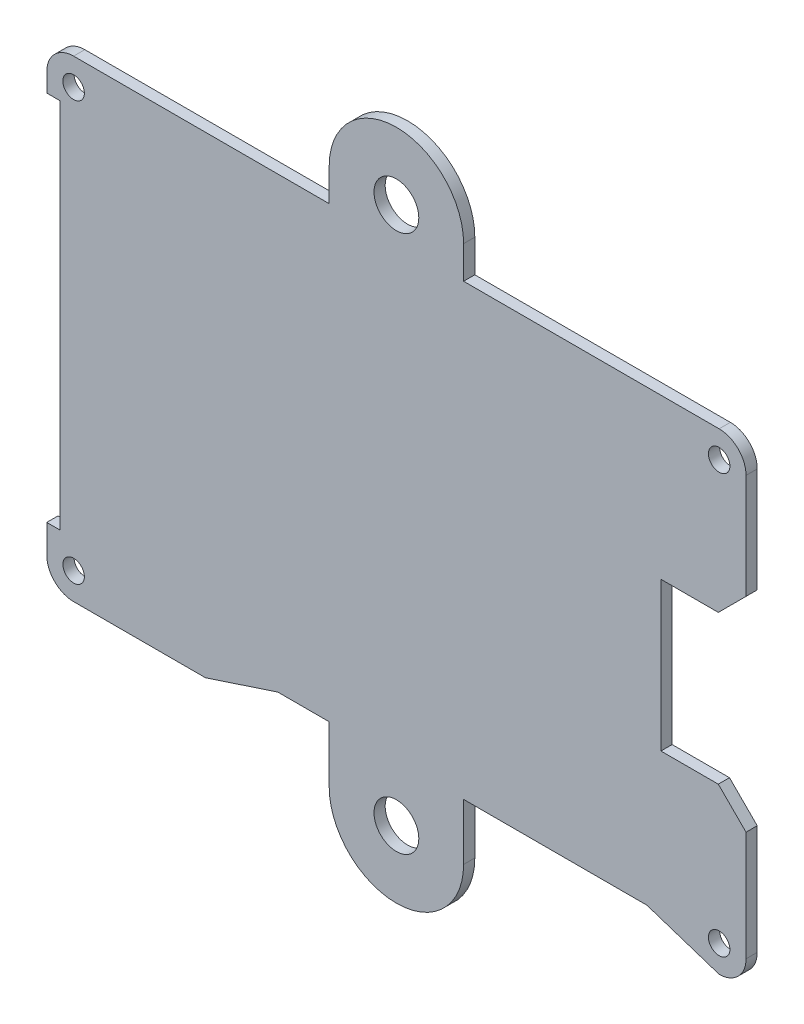
SolidWorks part; units mm, degrees
ref_plane "Front Plane" through (0, 0, 0) normal (0, 0, 1) x (1, 0, 0)
ref_plane "Top Plane" through (0, 0, 0) normal (0, 1, 0) x (1, 0, 0)
ref_plane "Right Plane" through (0, 0, 0) normal (1, 0, 0) x (0, 0, -1)
sketch "Sketch1" plane through (0, 0, 0) normal (0, 0, 1) x (1, 0, 0)
  line L0 (-301.9473, 111.7465) -> (-305.8779, 115.6771) construction
  line L1 (-305.8779, 115.6771) -> (-316.1078, 115.6771) construction
  line L2 (-316.1078, 115.6771) -> (-316.1078, 128.8851) construction
  line L3 (-316.1078, 128.8851) -> (-305.8779, 128.8851) construction
  line L4 (-305.8779, 128.8851) -> (-301.9473, 132.8157) construction
  line L5 (-301.9473, 132.8157) -> (-301.9473, 150.9704) construction
  line L6 (-305.7573, 154.7804) -> (-397.2471, 154.7804) construction
  line L7 (-401.0571, 150.9566) -> (-401.0571, 148.341) construction
  line L8 (-401.0571, 148.341) -> (-399.1521, 148.341) construction
  line L9 (-399.1521, 148.341) -> (-399.1521, 95.6449) construction
  line L10 (-399.1521, 95.6449) -> (-401.0571, 95.6449) construction
  line L11 (-401.0571, 95.6449) -> (-401.0571, 91.6593) construction
  line L12 (-397.2472, 87.8217) -> (-378.5565, 87.8217) construction
  line L13 (-378.5565, 87.8217) -> (-368.3165, 91.1883) construction
  line L14 (-368.3165, 91.1883) -> (-315.9973, 91.1883) construction
  line L15 (-315.9973, 91.1883) -> (-305.7573, 87.8217) construction
  line L16 (-301.9473, 91.6317) -> (-301.9473, 111.7465) construction
  line L17 (-301.9473, 111.7465) -> (-305.8779, 115.6771)
  line L18 (-305.8779, 115.6771) -> (-316.1078, 115.6771)
  line L19 (-316.1078, 115.6771) -> (-316.1078, 128.8851)
  line L20 (-316.1078, 128.8851) -> (-305.8779, 128.8851)
  line L21 (-305.8779, 128.8851) -> (-301.9473, 132.8157)
  line L22 (-301.9473, 132.8157) -> (-301.9473, 150.9704)
  line L23 (-305.7573, 154.7804) -> (-397.2471, 154.7804)
  line L24 (-401.0571, 150.9566) -> (-401.0571, 148.341)
  line L25 (-401.0571, 148.341) -> (-399.1521, 148.341)
  line L26 (-399.1521, 148.341) -> (-399.1521, 95.6449)
  line L27 (-399.1521, 95.6449) -> (-401.0571, 95.6449)
  line L28 (-401.0571, 95.6449) -> (-401.0571, 91.6593)
  line L29 (-397.2472, 87.8217) -> (-378.5565, 87.8217)
  line L30 (-378.5565, 87.8217) -> (-368.3165, 91.1883)
  line L31 (-368.3165, 91.1883) -> (-315.9973, 91.1883)
  line L32 (-315.9973, 91.1883) -> (-305.7573, 87.8217)
  line L33 (-301.9473, 91.6317) -> (-301.9473, 111.7465)
  circle A0 centre (-305.7573, 91.6317) radius 1.3559 construction
  circle A1 centre (-305.7573, 150.9704) radius 1.3559 construction
  circle A2 centre (-397.2471, 150.9704) radius 1.3559 construction
  circle A3 centre (-397.2472, 91.6317) radius 1.3559 construction
  circle A4 centre (-305.7573, 91.6317) radius 1.3559
  circle A5 centre (-305.7573, 150.9704) radius 1.3559
  circle A6 centre (-397.2471, 150.9704) radius 1.3559
  circle A7 centre (-397.2472, 91.6317) radius 1.3559
  arc A8 (-301.9473, 150.9704) -> (-305.7573, 154.7804) centre (-305.7573, 150.9704) ccw construction
  arc A9 (-397.2471, 154.7804) -> (-401.0571, 150.9566) centre (-397.2471, 150.9704) ccw construction
  arc A10 (-401.0571, 91.6593) -> (-397.2472, 87.8217) centre (-397.2472, 91.6317) ccw construction
  arc A11 (-305.7573, 87.8217) -> (-301.9473, 91.6317) centre (-305.7573, 91.6317) ccw construction
  arc A12 (-301.9473, 150.9704) -> (-305.7573, 154.7804) centre (-305.7573, 150.9704) ccw
  arc A13 (-397.2471, 154.7804) -> (-401.0571, 150.9566) centre (-397.2471, 150.9704) ccw
  arc A14 (-401.0571, 91.6593) -> (-397.2472, 87.8217) centre (-397.2472, 91.6317) ccw
  arc A15 (-305.7573, 87.8217) -> (-301.9473, 91.6317) centre (-305.7573, 91.6317) ccw
extrude "Boss-Extrude1" add sketch "Sketch1" along normal blind 1.5875
sketch "Sketch2" plane through (0, 0, 1.5875) normal (0, 0, 1) x (1, 0, 0)
  line L0 (-351.5022, 121.301) -> (-351.5022, 159.401) construction
  line L1 (-301.9473, 150.9704) -> (-301.9473, 91.6317) construction
  line L2 (-401.0571, 121.301) -> (-301.9473, 121.301) construction
  line L3 (-351.5022, 83.201) -> (-351.5022, 159.401) construction
  line L4 (-361.0272, 83.201) -> (-361.0272, 159.401)
  line L5 (-341.9772, 83.201) -> (-341.9772, 159.401)
  line L6 (-361.0272, 154.7804) -> (-341.9772, 154.7804)
  line L7 (-305.7573, 154.7804) -> (-397.2471, 154.7804) construction
  line L8 (-361.0272, 91.6317) -> (-341.9772, 91.6317)
  circle A0 centre (-351.5022, 159.401) radius 3.175
  arc A1 (-361.0272, 83.201) -> (-341.9772, 83.201) centre (-351.5022, 83.201) ccw
  arc A2 (-341.9772, 159.401) -> (-361.0272, 159.401) centre (-351.5022, 159.401) ccw
  circle A3 centre (-351.5022, 83.201) radius 3.175
  point P13 (-351.5022, 121.301)
  line M11 (-305.7573, 154.7804) -> (-397.2471, 154.7804)
  line M21 (-368.3165, 91.1883) -> (-315.9973, 91.1883)
  dimension "D1" = 6.35
  dimension "D2" = 38.1
  dimension "D3" = 19.05
extrude "Boss-Extrude2" add sketch "Sketch2" against normal blind 1.5875 contours L5 A2 L4 A0 M11 | L4 A1 L5 A3 M21
sketch "Sketch3" plane through (0, 0, 1.5875) normal (0, 0, 1) x (1, 0, 0)
  circle A0 centre (-397.2471, 150.9704) radius 1.524
  circle A1 centre (-305.7573, 150.9704) radius 1.524
  circle A2 centre (-305.7573, 91.6317) radius 1.524
  circle A3 centre (-397.2472, 91.6317) radius 1.524
  dimension "D1" = 3.048
extrude "Cut-Extrude1" cut sketch "Sketch3" against normal through all
sketch "Sketch4" plane through (0, 0, 1.5875) normal (0, 0, 1) x (1, 0, 0)
  line L0 (-301.9473, 136.1177) -> (-305.8779, 132.1871)
  line L1 (-301.9473, 132.8157) -> (-301.9473, 150.9704) construction
  line L2 (-305.8779, 132.1871) -> (-314.0123, 132.1871)
  line L3 (-314.0123, 132.1871) -> (-314.0123, 111.1051)
  line L4 (-314.0123, 111.1051) -> (-305.8779, 111.1051)
  line L5 (-305.8779, 111.1051) -> (-301.9473, 107.1745)
  line L6 (-301.9473, 91.6317) -> (-301.9473, 111.7465) construction
  line L7 (-301.9473, 136.1177) -> (-301.9473, 107.1745)
extrude "Cut-Extrude2" cut sketch "Sketch4" against normal through all
sketch "Sketch5" plane through (0, 0, 1.5875) normal (0, 0, 1) x (1, 0, 0)
  line L1 (-314.0123, 128.8851) -> (-316.1078, 128.8851)
  line L2 (-314.0123, 128.8851) -> (-314.0123, 115.6771)
  line L3 (-314.0123, 115.6771) -> (-316.1078, 115.6771)
  line L4 (-316.1078, 128.8851) -> (-316.1078, 115.6771)
extrude "Boss-Extrude3" add sketch "Sketch5" against normal up to vertex (1.5875 mm away) up to point (-301.9473, 136.1178, 0)
